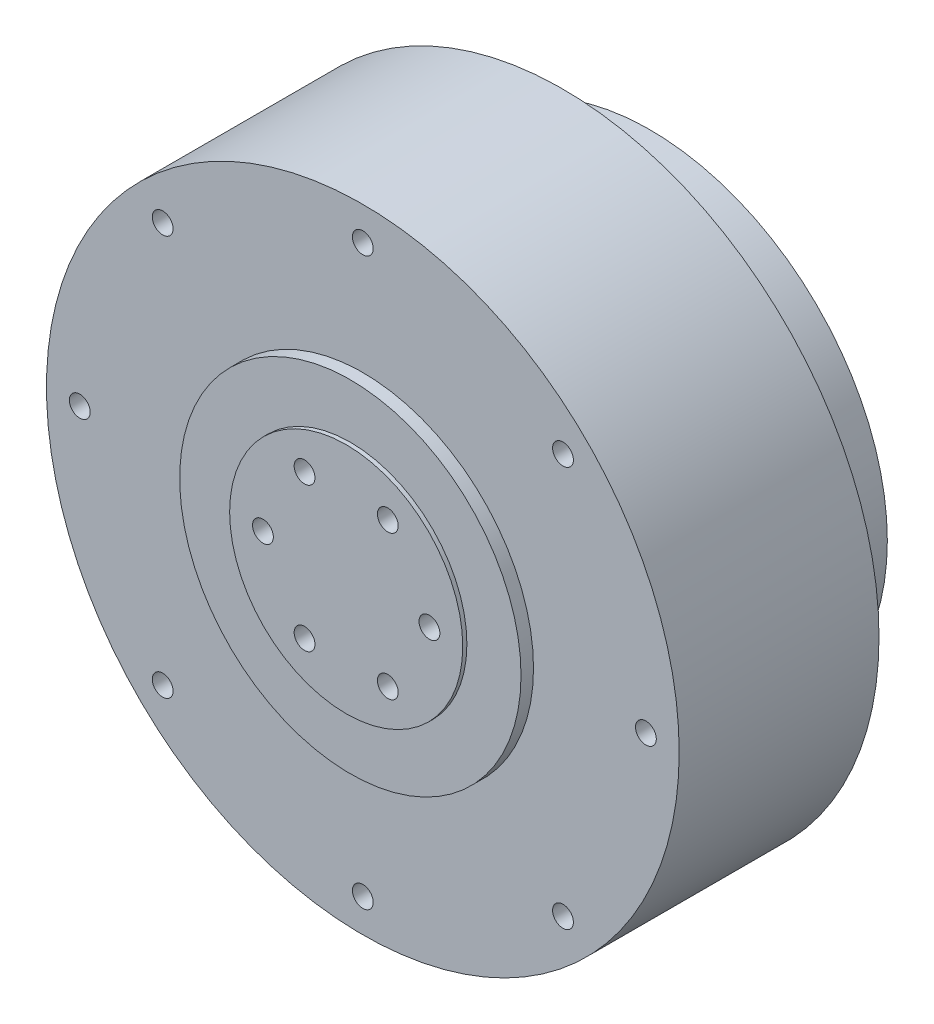
SolidWorks part; units mm, degrees
ref_plane "Front Plane" through (0, 0, 0) normal (0, 0, 1) x (1, 0, 0)
ref_plane "Top Plane" through (0, 0, 0) normal (0, 1, 0) x (1, 0, 0)
ref_plane "Right Plane" through (0, 0, 0) normal (1, 0, 0) x (0, 0, -1)
sketch "Sketch1" plane through (0, 0, 0) normal (1, 0, 0) x (0, 0, -1)
  line L0 (0, 0) -> (0, 14)
  line L1 (0, 14) -> (0.5, 14)
  line L2 (0.5, 14) -> (0.5, 20.5)
  line L3 (0.5, 20.5) -> (2, 20.5)
  line L4 (2, 20.5) -> (2, 38)
  line L5 (2, 38) -> (26, 38)
  line L6 (26, 38) -> (26, 28.5)
  line L7 (26, 28.5) -> (36.5, 28.5)
  line L8 (36.5, 28.5) -> (36.5, 0)
  line L9 (-42.7707, 0) -> (85.5811, 0) construction
  line L10 (0, 0) -> (36.5, 0)
  dimension "D1" = 14
  dimension "D2" = 0.5
  dimension "D3" = 6.5
  dimension "D4" = 1.5
  dimension "D5" = 17.5
  dimension "D6" = 24
  dimension "D7" = 10.5
  dimension "D8" = 28.5
  dimension "D9" = 36.5
  dimension "D10" = 38
revolve "Revolve1" add sketch "Sketch1" angle 360 about L9
hole_wizard "M3 Tapped Hole3" positions "Sketch2" profile "Sketch3" tap size "M3" standard "ISO"
sketch "Sketch2" plane through (0, 0, 0) normal (0, 0, 1) x (1, 0, 0)
  line L0 (0, 0) -> (-10, 0) construction
  circle A0 centre (0, 0) radius 10 construction
  point P0 (-10, 0)
  point P14 (-5, 8.6603)
  point P15 (5, 8.6603)
  point P16 (10, 0)
  point P17 (5, -8.6603)
  point P18 (-5, -8.6603)
  point P22 (0, 0)
  dimension "D1" = 20
  dimension "D3" = 10
  dimension "D4" = 60
  dimension "D2" = 6
sketch "Sketch3" plane through (-10, 0, 0) normal (1, 0, 0) x (0, -1, 0)
  line L0 (0, 0) -> (0, 8.2511)
  line L1 (0, 8.2511) -> (1.25, 7.5)
  line L2 (1.25, 7.5) -> (1.25, 0)
  line L5 (1.25, 0) -> (0, 0)
  line L10 (0, 8.2511) -> (-1.25, 7.5) construction
  line L11 (0, -6.35) -> (0, 107.95) construction
  dimension "Tap Drill Dia." = 2.5
  dimension "Tap Drill Depth" = 7.5
  dimension "Drill Angle" = 118
cosmetic thread "Hole Thread1" parameters "D1"=6, "D2"=3
cosmetic thread "Hole Thread2" parameters "D1"=6, "D2"=3
cosmetic thread "Hole Thread3" parameters "D1"=6, "D2"=3
cosmetic thread "Hole Thread4" parameters "D1"=6, "D2"=3
cosmetic thread "Hole Thread5" parameters "D1"=6, "D2"=3
cosmetic thread "Hole Thread6" parameters "D1"=6, "D2"=3
hole_wizard "M3 Tapped Hole1" positions "Sketch4" profile "Sketch5" tap size "M3" standard "ISO"
sketch "Sketch4" plane through (0, 0, -2) normal (0, 0, 1) x (1, 0, 0)
  line L0 (0, 0) -> (-34, 0) construction
  line L2 (0, 0) -> (-34, 0) construction
  circle A0 centre (0, 0) radius 34 construction
  point P0 (-34, 0)
  point P17 (-24.0416, 24.0416)
  point P18 (0, 34)
  point P19 (24.0416, 24.0416)
  point P20 (34, 0)
  point P21 (24.0416, -24.0416)
  point P22 (0, -34)
  point P23 (-24.0416, -24.0416)
  dimension "D1" = 68
  dimension "D3" = 34
  dimension "D4" = 45
  dimension "D2" = 8
sketch "Sketch5" plane through (-34, 0, -2) normal (1, 0, 0) x (0, -1, 0)
  line L0 (0, 0) -> (0, 3.7511)
  line L1 (0, 3.7511) -> (1.25, 3)
  line L2 (1.25, 3) -> (1.25, 0)
  line L5 (1.25, 0) -> (0, 0)
  line L10 (0, 3.7511) -> (-1.25, 3) construction
  line L11 (0, -6.35) -> (0, 107.95) construction
  dimension "Tap Drill Dia." = 2.5
  dimension "Tap Drill Depth" = 3
  dimension "Drill Angle" = 118
cosmetic thread "Hole Thread7" parameters "D1"=6, "D2"=3
cosmetic thread "Hole Thread8" parameters "D1"=6, "D2"=3
hole_wizard "M3 Tapped Hole2" positions "Sketch7" profile "Sketch8" tap size "M3" standard "ISO"
sketch "Sketch7" plane through (0, 0, -26) normal (0, 0, -1) x (-1, 0, 0)
  line L0 (0, 0) -> (-34, 0) construction
  line L2 (0, 0) -> (-34, 0) construction
  circle A0 centre (0, 0) radius 34 construction
  point P0 (-34, 0)
  point P16 (-24.0416, 24.0416)
  point P17 (0, 34)
  point P18 (24.0416, 24.0416)
  point P19 (34, 0)
  point P20 (24.0416, -24.0416)
  point P21 (0, -34)
  point P22 (-24.0416, -24.0416)
  dimension "D1" = 68
  dimension "D3" = 34
  dimension "D4" = 45
  dimension "D2" = 8
sketch "Sketch8" plane through (34, 0, -26) normal (1, 0, 0) x (0, 1, 0)
  line L0 (0, 0) -> (0, 3.7511)
  line L1 (0, 3.7511) -> (1.25, 3)
  line L2 (1.25, 3) -> (1.25, 0)
  line L5 (1.25, 0) -> (0, 0)
  line L10 (0, 3.7511) -> (-1.25, 3) construction
  line L11 (0, -6.35) -> (0, 107.95) construction
  dimension "Tap Drill Dia." = 2.5
  dimension "Tap Drill Depth" = 3
  dimension "Drill Angle" = 118
cosmetic thread "Hole Thread15" parameters "D1"=6, "D2"=3
cosmetic thread "Hole Thread16" parameters "D1"=6, "D2"=3
cosmetic thread "Hole Thread23" parameters "D1"=6, "D2"=3
cosmetic thread "Hole Thread24" parameters "D1"=6, "D2"=3
cosmetic thread "Hole Thread25" parameters "D1"=6, "D2"=3
cosmetic thread "Hole Thread26" parameters "D1"=6, "D2"=3
cosmetic thread "Hole Thread27" parameters "D1"=6, "D2"=3
cosmetic thread "Hole Thread28" parameters "D1"=6, "D2"=3
